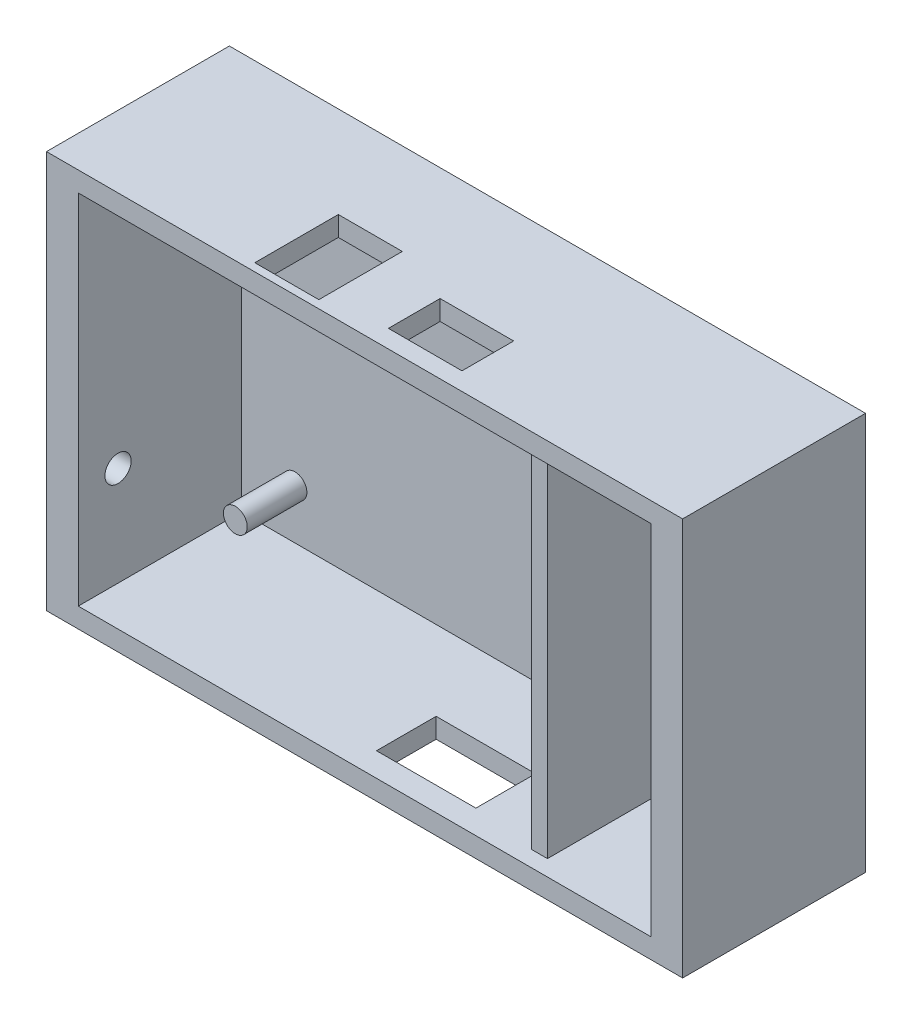
SolidWorks part; units mm, degrees
ref_plane "Plan de face" through (0, 0, 0) normal (0, 0, 1) x (1, 0, 0)
ref_plane "Plan de dessus" through (0, 0, 0) normal (0, 1, 0) x (1, 0, 0)
ref_plane "Plan de droite" through (0, 0, 0) normal (1, 0, 0) x (0, 0, -1)
sketch "Esquisse1" plane through (0, 0, 0) normal (0, 0, 1) x (1, 0, 0)
  line L1 (72, 45) -> (-72, 45)
  line L2 (72, 45) -> (72, -45)
  line L3 (72, -45) -> (-72, -45)
  line L4 (-72, 45) -> (-72, -45)
  line L5 (72, 45) -> (-72, -45) construction
  line L6 (72, -45) -> (-72, 45) construction
  line L7 (-80, 50) -> (80, 50)
  line L8 (-80, 50) -> (-80, -50)
  line L9 (-80, -50) -> (80, -50)
  line L10 (80, 50) -> (80, -50)
  line L11 (-80, 50) -> (80, -50) construction
  line L12 (-80, -50) -> (80, 50) construction
  point P0 (0, 0)
  point P6 (0, 0)
  dimension "D1" = 160
  dimension "D2" = 144
  dimension "D3" = 100
  dimension "D4" = 90
extrude "profondeur boitier" add sketch "Esquisse1" along normal blind 46
sketch "Esquisse2" plane through (0, 0, 0) normal (0, 0, 1) x (1, 0, 0)
  line L1 (-72, 45) -> (72, 45)
  line L2 (-72, 45) -> (-72, -45)
  line L3 (-72, -45) -> (72, -45)
  line L4 (72, 45) -> (72, -45)
  line L5 (-72, 45) -> (72, -45) construction
  line L6 (-72, -45) -> (72, 45) construction
  point P0 (0, 0)
extrude "profondeur fond" add sketch "Esquisse2" along normal blind 5
sketch "Esquisse3" plane through (0, 0, 0) normal (0, 0, 1) x (1, 0, 0)
  line L0 (72, 45) -> (-72, 45) construction
  line L1 (38, 45) -> (42, 45)
  line L2 (38, 45) -> (38, -45)
  line L3 (38, -45) -> (42, -45)
  line L4 (42, 45) -> (42, -45)
  line L5 (-72, -45) -> (72, -45) construction
  line L6 (72, -45) -> (72, 45) construction
  line L7 (-72, 45) -> (-72, -45) construction
  dimension "D1" = 4
  dimension "D2" = 30
  dimension "D3" = 110
extrude "Séparation platine batterie" add sketch "Esquisse3" along normal blind 42
sketch "Esquisse7" plane through (0, 0, 0) normal (1, 0, 0) x (0, 0, -1)
  line L0 (-46, -50) -> (-46, 50) construction
  line L1 (-46, 50) -> (0, 50) construction
  circle A0 centre (-36, -20) radius 3.3
  dimension "D1" = 6.6
  dimension "D2" = 10
  dimension "D3" = 70
extrude "Antenne LoRA" cut sketch "Esquisse7" against normal blind 92
sketch "Esquisse8" plane through (0, 0, 0) normal (0, 1, 0) x (1, 0, 0)
  line L0 (80, -46) -> (-80, -46) construction
  line L1 (1.5, -28.5) -> (20, -28.5)
  line L2 (1.5, -28.5) -> (1.5, -41.5)
  line L3 (1.5, -41.5) -> (20, -41.5)
  line L4 (20, -28.5) -> (20, -41.5)
  line L5 (80, 0) -> (-80, 0) construction
  line L6 (80, -46) -> (80, 0) construction
  point P8 (20, -35)
  dimension "D1" = 4.5
  dimension "D2" = 13
  dimension "D3" = 28.5
  dimension "D4" = 18.5
  dimension "D5" = 60
extrude "interrupteur" cut sketch "Esquisse8" along normal blind 92
sketch "Esquisse9" plane through (0, 0, 0) normal (0, 0, 1) x (1, 0, 0)
  line L0 (-58.5, 32.5) -> (-58.5, 45)
  line L1 (38, 45) -> (-72, 45) construction
  line L2 (24.5, 32.5) -> (24.5, 45)
  line L3 (-58.5, -32.5) -> (-58.5, -45)
  line L4 (-72, -45) -> (72, -45) construction
  line L5 (-72, -45) -> (38, -45) construction
  line L6 (-58.5, 32.5) -> (-72, 32.5)
  line L7 (-72, 45) -> (-72, -45) construction
  line L8 (24.5, 32.5) -> (38, 32.5)
  line L9 (38, -45) -> (38, 45) construction
  circle A0 centre (-58.5, -32.5) radius 3
  circle A1 centre (24.5, -32.5) radius 3
  circle A2 centre (24.5, 32.5) radius 3
  circle A3 centre (-58.5, 32.5) radius 3
  dimension "D1" = 6
  dimension "D2" = 83
  dimension "D3" = 65
extrude "Vis platine" add sketch "Esquisse9" along normal blind 20 contours A3 | A2 | A0 | A1
sketch "Esquisse10" plane through (0, 0, 0) normal (0, 1, 0) x (1, 0, 0)
  line L0 (1.5, -28.5) -> (1.5, -41.5) construction
  line L1 (-29.6, -23) -> (-13.5, -23)
  line L2 (-29.6, -23) -> (-29.6, -44)
  line L3 (-29.6, -44) -> (-13.5, -44)
  line L4 (-13.5, -23) -> (-13.5, -44)
  line L5 (80, -46) -> (-80, -46) construction
  dimension "D1" = 21
  dimension "D2" = 16.1
  dimension "D3" = 21
  dimension "D4" = 15
  dimension "D5" = 2
extrude "DHT22" cut sketch "Esquisse10" along normal blind 92
sketch "Esquisse11" plane through (0, 0, 0) normal (0, 1, 0) x (1, 0, 0)
  line L0 (80, -46) -> (-80, -46) construction
  line L1 (-3, -25) -> (22, -25)
  line L2 (-3, -25) -> (-3, -40)
  line L3 (-3, -40) -> (22, -40)
  line L4 (22, -25) -> (22, -40)
  line L5 (80, -46) -> (80, 0) construction
  dimension "D1" = 25
  dimension "D2" = 15
  dimension "D3" = 6
  dimension "D4" = 58
extrude "DB9" cut sketch "Esquisse11" against normal blind 92
